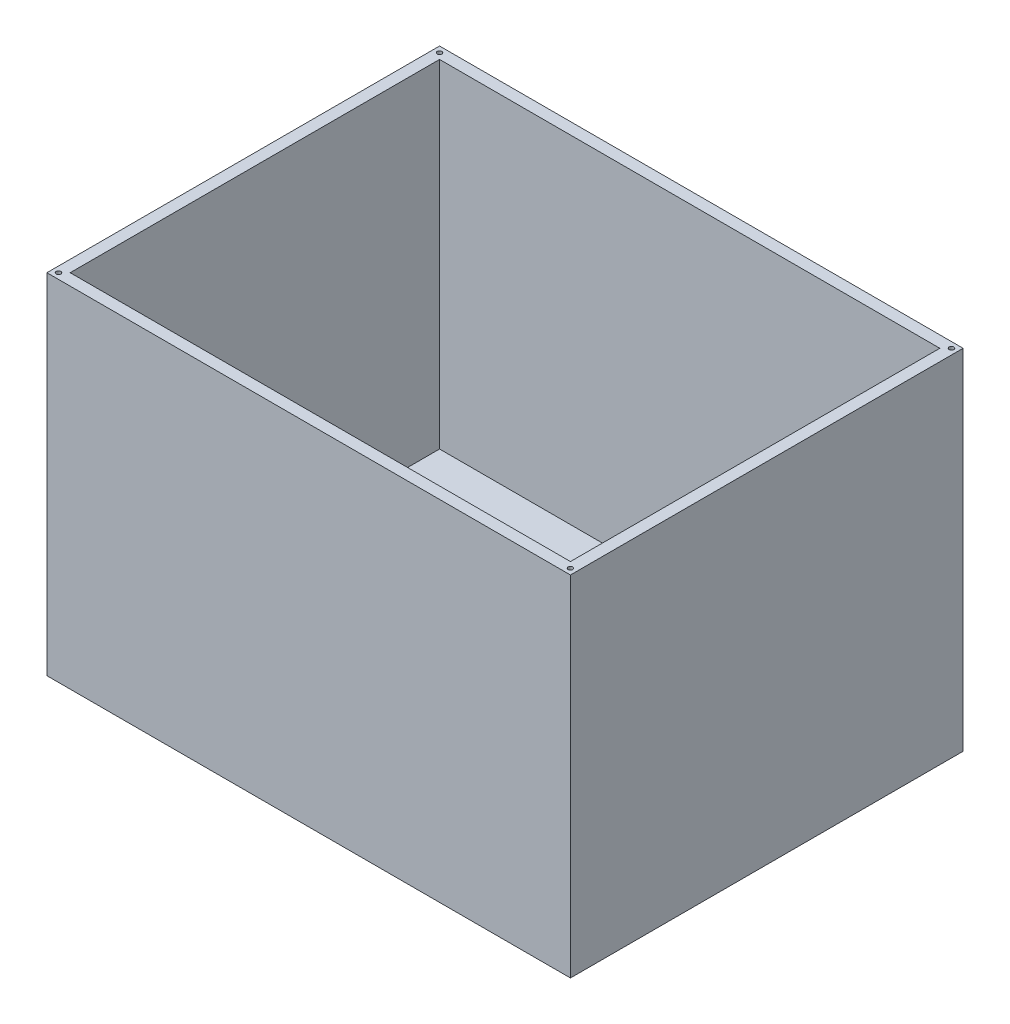
SolidWorks part; units mm, degrees
ref_plane "Front Plane" through (0, 0, 0) normal (0, 0, 1) x (1, 0, 0)
ref_plane "Top Plane" through (0, 0, 0) normal (0, 1, 0) x (1, 0, 0)
ref_plane "Right Plane" through (0, 0, 0) normal (1, 0, 0) x (0, 0, -1)
sketch "Sketch1" plane through (0, 0, 0) normal (0, 1, 0) x (1, 0, 0)
  line L1 (-450, 337.5) -> (450, 337.5)
  line L2 (-450, 337.5) -> (-450, -337.5)
  line L3 (-450, -337.5) -> (450, -337.5)
  line L4 (450, 337.5) -> (450, -337.5)
  line L5 (-450, 337.5) -> (450, -337.5) construction
  line L6 (-450, -337.5) -> (450, 337.5) construction
  point P0 (0, 0)
extrude "Boss-Extrude1" add sketch "Sketch1" along normal blind 600
shell "Shell1" thickness 20
sketch "Sketch3" plane through (0, 600, 0) normal (0, 1, 0) x (1, 0, 0)
  line L0 (-450, -337.5) -> (-430, -317.5) construction
  line L1 (-450, -337.5) -> (-430, -337.5)
  line L2 (-450, -337.5) -> (-450, -317.5)
  line L3 (-450, -317.5) -> (-430, -317.5)
  line L4 (-430, -337.5) -> (-430, -317.5)
  line L5 (-450, -317.5) -> (-430, -337.5) construction
sketch "Sketch5" plane through (0, 600, 0) normal (0, 1, 0) x (1, 0, 0)
  line L0 (-450, -337.5) -> (-430, -317.5) construction
  circle A0 centre (-440, -327.5) radius 4
extrude "Cut-Extrude1" cut sketch "Sketch5" against normal blind 20
sketch "Sketch6" plane through (0, 600, 0) normal (0, 1, 0) x (1, 0, 0)
  line L0 (430, -317.5) -> (450, -337.5) construction
  circle A0 centre (440, -327.5) radius 4
extrude "Cut-Extrude2" cut sketch "Sketch6" against normal blind 20
sketch "Sketch7" plane through (0, 600, 0) normal (0, 1, 0) x (1, 0, 0)
  line L0 (430, 317.5) -> (450, 337.5) construction
  circle A0 centre (440, 327.5) radius 4
extrude "Cut-Extrude3" cut sketch "Sketch7" against normal blind 20
sketch "Sketch8" plane through (0, 600, 0) normal (0, 1, 0) x (1, 0, 0)
  line L0 (-430, 317.5) -> (-450, 337.5) construction
  circle A0 centre (-440, 327.5) radius 4
extrude "Cut-Extrude4" cut sketch "Sketch8" against normal blind 20
